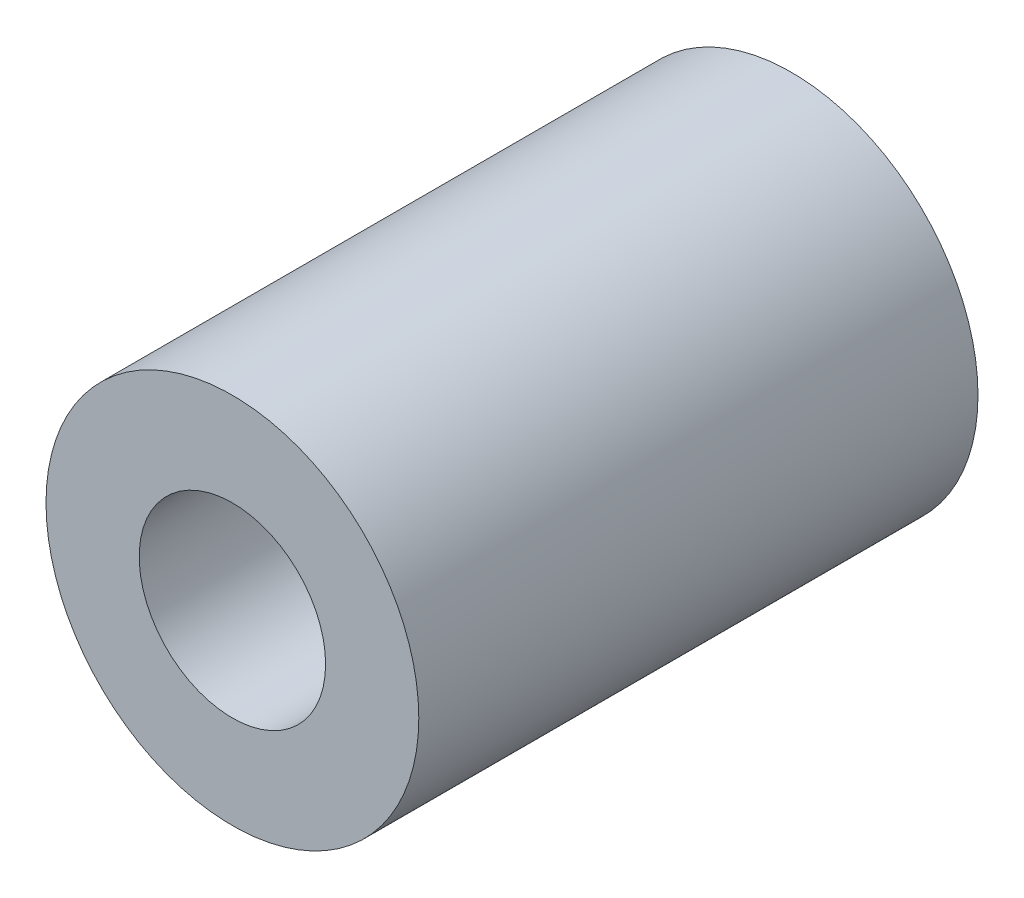
SolidWorks part; units mm, degrees
ref_plane "前视基准面" through (0, 0, 0) normal (0, 0, 1) x (1, 0, 0)
ref_plane "上视基准面" through (0, 0, 0) normal (0, 1, 0) x (1, 0, 0)
ref_plane "右视基准面" through (0, 0, 0) normal (1, 0, 0) x (0, 0, -1)
other "Configuration Table"
sketch "草图2" plane through (0, 0, 0) normal (0, 0, 1) x (1, 0, 0)
  circle A0 centre (0, 0) radius 1.5
  circle A1 centre (0, 0) radius 3
  dimension "D1" = 3
  dimension "D2" = 6
extrude "凸台-拉伸1" add sketch "草图2" along normal blind 9
